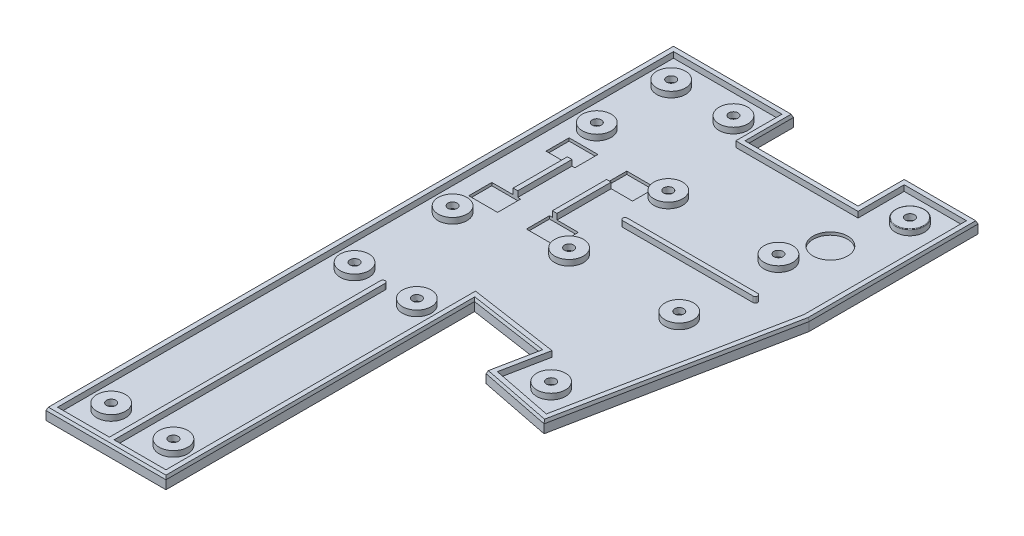
SolidWorks part; units mm, degrees
ref_plane "Front Plane" through (0, 0, 0) normal (0, 0, 1) x (1, 0, 0)
ref_plane "Top Plane" through (0, 0, 0) normal (0, 1, 0) x (1, 0, 0)
ref_plane "Right Plane" through (0, 0, 0) normal (1, 0, 0) x (0, 0, -1)
ref_plane "Plane1" through (0, 2, 0) normal (0, 1, 0) x (1, 0, 0)
sketch "Sketch1" plane through (0, 2, 0) normal (0, 1, 0) x (1, 0, 0)
  line L0 (24.2179, -38.1965) -> (31.8, -0.0788)
  line L1 (31.8, -0.0788) -> (31.8, 28.9813)
  line L2 (31.8, 28.9813) -> (19.4, 28.9813)
  line L3 (19.4, 28.9813) -> (19.4, 20.9813)
  line L4 (19.4, 20.9813) -> (-0.2, 20.9813)
  line L5 (-0.2, 20.9813) -> (-0.2, 28.9813)
  line L6 (-0.2, 28.9813) -> (-20.6, 28.9813)
  line L7 (-20.6, 28.9813) -> (-20.6, -79.4187)
  line L8 (-20.6, -79.4187) -> (-0.2, -79.4187)
  line L9 (-0.2, -79.4187) -> (-0.2, -25.8749)
  line L10 (-0.2, -25.8749) -> (13.6189, -27.9212)
  line L11 (13.6189, -27.9212) -> (12.0562, -35.7774)
  line L12 (12.0562, -35.7774) -> (24.2179, -38.1965)
extrude "Boss-Extrude1" add sketch "Sketch1" against normal blind 0.5 draft 21.801 draft outward yes
sketch "Sketch2" plane through (0, 1.5, 0) normal (0, -1, 0) x (1, 0, 0)
  line L0 (32, -29.1813) -> (19.2, -29.1813)
  line L1 (19.2, -29.1813) -> (19.2, -21.1813)
  line L2 (19.2, -21.1813) -> (0, -21.1813)
  line L3 (0, -21.1813) -> (0, -29.1813)
  line L4 (0, -29.1813) -> (-20.8, -29.1813)
  line L5 (-20.8, -29.1813) -> (-20.8, 79.6187)
  line L6 (-20.8, 79.6187) -> (0, 79.6187)
  line L7 (0, 79.6187) -> (0, 26.1067)
  line L8 (0, 26.1067) -> (13.3817, 28.0883)
  line L9 (13.3817, 28.0883) -> (11.821, 35.9345)
  line L10 (11.821, 35.9345) -> (24.3751, 38.4317)
  line L11 (24.3751, 38.4317) -> (32, 0.0985)
  line L12 (32, 0.0985) -> (32, -29.1813)
extrude "Boss-Extrude2" add sketch "Sketch2" along normal blind 1.5
sketch "Sketch3" plane through (0, 2, 0) normal (0, 1, 0) x (-1, 0, 0)
  line L0 (19.8, -28.1813) -> (19.8, 78.6187)
  line L1 (19.8, 78.6187) -> (1, 78.6187)
  line L2 (1, 78.6187) -> (1, 24.9477)
  line L3 (1, 24.9477) -> (-15.026, 24.9477)
  line L4 (-15.026, 24.9477) -> (-12.9969, 35.1488)
  line L5 (-12.9969, 35.1488) -> (-23.5894, 37.2558)
  line L6 (-23.5894, 37.2558) -> (-31, 0)
  line L7 (-31, 0) -> (-31, -28.1813)
  line L8 (-31, -28.1813) -> (-20.2, -28.1813)
  line L9 (-20.2, -28.1813) -> (-20.2, -20.1813)
  line L10 (-20.2, -20.1813) -> (1, -20.1813)
  line L11 (1, -20.1813) -> (1, -28.1813)
  line L12 (1, -28.1813) -> (19.8, -28.1813)
extrude "Cut-Extrude1" cut sketch "Sketch3" against normal blind 1
sketch "Sketch4" plane through (0, 1, 0) normal (0, 1, 0) x (-1, 0, 0)
  line L0 (6.9, 6.2187) -> (6.9, 10.2187)
  line L1 (6.9, 10.2187) -> (1.9, 10.2187)
  line L2 (1.9, 10.2187) -> (1.9, 6.2187)
  line L3 (1.9, 6.2187) -> (6.9, 6.2187)
extrude "Cut-Extrude2" cut sketch "Sketch4" against normal blind 0.5
sketch "Sketch5" plane through (0, 1, 0) normal (0, 1, 0) x (-1, 0, 0)
  line L0 (6.4, -3.1813) -> (5.6, -3.1813)
  line L1 (5.6, -3.1813) -> (5.6, 6.2187)
  line L2 (5.6, 6.2187) -> (6.4, 6.2187)
  line L3 (6.4, 6.2187) -> (6.4, -3.1813)
extrude "Boss-Extrude3" add sketch "Sketch5" along normal blind 1
sketch "Sketch6" plane through (0, 1, 0) normal (0, 1, 0) x (-1, 0, 0)
  line L0 (6.9, -3.1813) -> (1.9, -3.1813)
  line L1 (1.9, -3.1813) -> (1.9, -7.1813)
  line L2 (1.9, -7.1813) -> (6.9, -7.1813)
  line L3 (6.9, -7.1813) -> (6.9, -3.1813)
extrude "Cut-Extrude3" cut sketch "Sketch6" against normal blind 0.5
sketch "Sketch7" plane through (0, 1, 0) normal (0, 1, 0) x (-1, 0, 0)
  line L0 (16.9, 6.2187) -> (16.9, 10.2187)
  line L1 (16.9, 10.2187) -> (11.9, 10.2187)
  line L2 (11.9, 10.2187) -> (11.9, 6.2187)
  line L3 (11.9, 6.2187) -> (16.9, 6.2187)
extrude "Cut-Extrude4" cut sketch "Sketch7" against normal blind 0.5
sketch "Sketch8" plane through (0, 1, 0) normal (0, 1, 0) x (-1, 0, 0)
  line L0 (12.4, 6.2187) -> (13.2, 6.2187)
  line L1 (13.2, 6.2187) -> (13.2, -3.1813)
  line L2 (13.2, -3.1813) -> (12.4, -3.1813)
  line L3 (12.4, -3.1813) -> (12.4, 6.2187)
extrude "Boss-Extrude4" add sketch "Sketch8" along normal blind 1
sketch "Sketch9" plane through (0, 1, 0) normal (0, 1, 0) x (-1, 0, 0)
  line L0 (16.9, -3.1813) -> (11.9, -3.1813)
  line L1 (11.9, -3.1813) -> (11.9, -7.1813)
  line L2 (11.9, -7.1813) -> (16.9, -7.1813)
  line L3 (16.9, -7.1813) -> (16.9, -3.1813)
extrude "Cut-Extrude5" cut sketch "Sketch9" against normal blind 0.5
sketch "Sketch10" plane through (0, 1, 0) normal (0, 1, 0) x (-1, 0, 0)
  line L0 (10.8, 78.6187) -> (10.8, 31.6187)
  line L1 (10, 31.6187) -> (10, 78.6187)
  line L2 (10, 78.6187) -> (10.8, 78.6187)
  arc A0 (10.8, 31.6187) -> (10, 31.6187) centre (10.4, 31.6187) cw
extrude "Boss-Extrude5" add sketch "Sketch10" along normal blind 1
sketch "Sketch11" plane through (0, 1, 0) normal (0, 1, 0) x (-1, 0, 0)
  line L0 (-1.2, 0.8187) -> (-23.8, 0.8187)
  line L1 (-23.8, 1.6187) -> (-1.2, 1.6187)
  arc A0 (-23.8, 0.8187) -> (-23.8, 1.6187) centre (-23.8, 1.2187) cw
  arc A1 (-1.2, 1.6187) -> (-1.2, 0.8187) centre (-1.2, 1.2187) cw
extrude "Boss-Extrude6" add sketch "Sketch11" along normal blind 1
draft "Draft1" type of draft neutral plane draft angle 8.423 faces to draft 1 face at (7.013, 1.5, 24.9477) neutral plane through (-1, 1, 78.6187) neutral plane normal (-1, 0, 0) reverse direction yes parameters "D1"=8.423
ref_plane "Plane2" through (0, 0, -6.8813) normal (0, 0, 1) x (1, 0, 0)
sketch "Sketch12" plane through (0, 0, -6.8813) normal (0, 0, 1) x (1, 0, 0)
  line L0 (3.1, 2) -> (0.6, 2)
  line L1 (0.6, 2) -> (0.6, 1)
  line L2 (0.6, 1) -> (3.1, 1)
  line L3 (3.1, 1) -> (3.1, 2)
  line L4 (0.6, 2) -> (0.6, 1) construction
revolve "Revolve1" add sketch "Sketch12" angle 360 about L4
ref_plane "Plane3" through (0, 0, 73.3187) normal (0, 0, 1) x (1, 0, 0)
sketch "Sketch13" plane through (0, 0, 73.3187) normal (0, 0, 1) x (1, 0, 0)
  line L0 (-13.3, 2) -> (-15.8, 2)
  line L1 (-15.8, 2) -> (-15.8, 1)
  line L2 (-15.8, 1) -> (-13.3, 1)
  line L3 (-13.3, 1) -> (-13.3, 2)
  line L4 (-15.8, 2) -> (-15.8, 1) construction
revolve "Revolve2" add sketch "Sketch13" angle 360 about L4
sketch "Sketch14" plane through (0, 0, 73.3187) normal (0, 0, 1) x (1, 0, 0)
  line L0 (-2.5, 2) -> (-5, 2)
  line L1 (-5, 2) -> (-5, 1)
  line L2 (-5, 1) -> (-2.5, 1)
  line L3 (-2.5, 1) -> (-2.5, 2)
  line L4 (-5, 2) -> (-5, 1) construction
revolve "Revolve3" add sketch "Sketch14" angle 360 about L4
ref_plane "Plane4" through (0, 0, 31.1187) normal (0, 0, 1) x (1, 0, 0)
sketch "Sketch15" plane through (0, 0, 31.1187) normal (0, 0, 1) x (1, 0, 0)
  line L0 (-13.3, 2) -> (-15.8, 2)
  line L1 (-15.8, 2) -> (-15.8, 1)
  line L2 (-15.8, 1) -> (-13.3, 1)
  line L3 (-13.3, 1) -> (-13.3, 2)
  line L4 (-15.8, 2) -> (-15.8, 1) construction
revolve "Revolve4" add sketch "Sketch15" angle 360 about L4
sketch "Sketch16" plane through (0, 0, 31.1187) normal (0, 0, 1) x (1, 0, 0)
  line L0 (-2.5, 2) -> (-5, 2)
  line L1 (-5, 2) -> (-5, 1)
  line L2 (-5, 1) -> (-2.5, 1)
  line L3 (-2.5, 1) -> (-2.5, 2)
  line L4 (-5, 2) -> (-5, 1) construction
revolve "Revolve5" add sketch "Sketch16" angle 360 about L4
ref_plane "Plane5" through (0, 0, 14.1187) normal (0, 0, 1) x (1, 0, 0)
sketch "Sketch17" plane through (0, 0, 14.1187) normal (0, 0, 1) x (1, 0, 0)
  line L0 (-13.3, 2) -> (-15.8, 2)
  line L1 (-15.8, 2) -> (-15.8, 1)
  line L2 (-15.8, 1) -> (-13.3, 1)
  line L3 (-13.3, 1) -> (-13.3, 2)
  line L4 (-15.8, 2) -> (-15.8, 1) construction
revolve "Revolve6" add sketch "Sketch17" angle 360 about L4
ref_plane "Plane6" through (0, 0, -10.8813) normal (0, 0, 1) x (1, 0, 0)
sketch "Sketch18" plane through (0, 0, -10.8813) normal (0, 0, 1) x (1, 0, 0)
  line L0 (-13.3, 2) -> (-15.8, 2)
  line L1 (-15.8, 2) -> (-15.8, 1)
  line L2 (-15.8, 1) -> (-13.3, 1)
  line L3 (-13.3, 1) -> (-13.3, 2)
  line L4 (-15.8, 2) -> (-15.8, 1) construction
revolve "Revolve7" add sketch "Sketch18" angle 360 about L4
ref_plane "Plane7" through (0, 0, -23.7813) normal (0, 0, 1) x (1, 0, 0)
sketch "Sketch19" plane through (0, 0, -23.7813) normal (0, 0, 1) x (1, 0, 0)
  line L0 (-13.3, 2) -> (-15.8, 2)
  line L1 (-15.8, 2) -> (-15.8, 1)
  line L2 (-15.8, 1) -> (-13.3, 1)
  line L3 (-13.3, 1) -> (-13.3, 2)
  line L4 (-15.8, 2) -> (-15.8, 1) construction
revolve "Revolve8" add sketch "Sketch19" angle 360 about L4
sketch "Sketch20" plane through (0, 0, -23.7813) normal (0, 0, 1) x (1, 0, 0)
  line L0 (-2.5, 2) -> (-5, 2)
  line L1 (-5, 2) -> (-5, 1)
  line L2 (-5, 1) -> (-2.5, 1)
  line L3 (-2.5, 1) -> (-2.5, 2)
  line L4 (-5, 2) -> (-5, 1) construction
revolve "Revolve9" add sketch "Sketch20" angle 360 about L4
sketch "Sketch21" plane through (0, 0, -23.7813) normal (0, 0, 1) x (1, 0, 0)
  line L0 (28.1, 2) -> (25.6, 2)
  line L1 (25.6, 2) -> (25.6, 1)
  line L2 (25.6, 1) -> (28.1, 1)
  line L3 (28.1, 1) -> (28.1, 2)
  line L4 (25.6, 2) -> (25.6, 1) construction
revolve "Revolve10" add sketch "Sketch21" angle 360 about L4
sketch "Sketch22" plane through (0, 0, -6.8813) normal (0, 0, 1) x (1, 0, 0)
  line L0 (22.2, 2) -> (19.7, 2)
  line L1 (19.7, 2) -> (19.7, 1)
  line L2 (19.7, 1) -> (22.2, 1)
  line L3 (22.2, 1) -> (22.2, 2)
  line L4 (19.7, 2) -> (19.7, 1) construction
revolve "Revolve11" add sketch "Sketch22" angle 360 about L4
ref_plane "Plane8" through (0, 0, 10.3187) normal (0, 0, 1) x (1, 0, 0)
sketch "Sketch23" plane through (0, 0, 10.3187) normal (0, 0, 1) x (1, 0, 0)
  line L0 (22.2, 2) -> (19.7, 2)
  line L1 (19.7, 2) -> (19.7, 1)
  line L2 (19.7, 1) -> (22.2, 1)
  line L3 (22.2, 1) -> (22.2, 2)
  line L4 (19.7, 2) -> (19.7, 1) construction
revolve "Revolve12" add sketch "Sketch23" angle 360 about L4
ref_plane "Plane9" through (0, 0, 31.9722) normal (0, 0, 1) x (1, 0, 0)
sketch "Sketch24" plane through (0, 0, 31.9722) normal (0, 0, 1) x (1, 0, 0)
  line L0 (21.6345, 2) -> (19.1345, 2)
  line L1 (19.1345, 2) -> (19.1345, 1)
  line L2 (19.1345, 1) -> (21.6345, 1)
  line L3 (21.6345, 1) -> (21.6345, 2)
  line L4 (19.1345, 2) -> (19.1345, 1) construction
revolve "Revolve13" add sketch "Sketch24" angle 360 about L4
sketch "Sketch25" plane through (0, 0, 10.3187) normal (0, 0, 1) x (1, 0, 0)
  line L0 (3.1, 2) -> (0.6, 2)
  line L1 (0.6, 2) -> (0.6, 1)
  line L2 (0.6, 1) -> (3.1, 1)
  line L3 (3.1, 1) -> (3.1, 2)
  line L4 (0.6, 2) -> (0.6, 1) construction
revolve "Revolve14" add sketch "Sketch25" angle 360 about L4
hole_wizard "M3x0.5 Tapped Hole1" positions "Sketch27" profile "Sketch26" tap size "M3x0.5" standard "ANSI Metric"
sketch "Sketch27" plane through (0, 0, 0) normal (0, -1, 0) x (-1, 0, 0)
  point P0 (15.8, 10.8813)
  point P1 (5, 23.7813)
  point P2 (-19.7, 6.8813)
  point P3 (-19.1345, -31.9722)
  point P4 (15.8, -14.1187)
  point P5 (15.8, -31.1187)
  point P6 (15.8, -73.3187)
  point P7 (5, -73.3187)
  point P8 (5, -31.1187)
  point P9 (-0.6, -10.3187)
  point P10 (-19.7, -10.3187)
  point P11 (-25.6, 23.7813)
  point P12 (15.8, 23.7813)
  point P13 (-0.6, 6.8813)
sketch "Sketch26" plane through (-15.8, 0, -10.8813) normal (1, 0, 0) x (0, 0, -1)
  line L0 (0, 0) -> (0, 2)
  line L1 (0, 2) -> (0.8, 2)
  line L3 (0.8, 2) -> (0.8, 1)
  line L4 (0.8, 1) -> (1.5, 1)
  line L5 (1.5, 1) -> (1.5, 0)
  line L7 (1.5, 0) -> (0, 0)
  line L11 (0, -6.35) -> (0, 107.95) construction
  dimension "Thru Tap Drill Dia." = 1.6
  dimension "Thru Tap Drill Depth" = 2
  dimension "Thread Major Dia." = 3
  dimension "Thread Depth" = 1
hole_wizard "Ø6.0 (6) Diameter Hole1" positions "Sketch29" profile "Sketch28" hole size "Ø6.0" standard "ANSI Metric"
sketch "Sketch29" plane through (0, 1, 0) normal (0, 1, 0) x (1, 0, 0)
  point P0 (22, 13.5813)
sketch "Sketch28" plane through (22, 1, -13.5813) normal (1, 0, 0) x (0, 0, 1)
  line L0 (0, 0) -> (0, 0.5)
  line L1 (0, 0.5) -> (3, 0.5)
  line L2 (3, 0.5) -> (3, 0)
  line L5 (3, 0) -> (0, 0)
  line L10 (0, 0.5) -> (-3, 0.5) construction
  line L11 (0, -6.35) -> (0, 107.95) construction
  dimension "Hole Dia." = 6
  dimension "Hole Depth" = 0.5
  dimension "Drill Angle" = 180
fillet "Fillet2" radius 0.1 1 edges at (28.1, 2, -23.7813)
